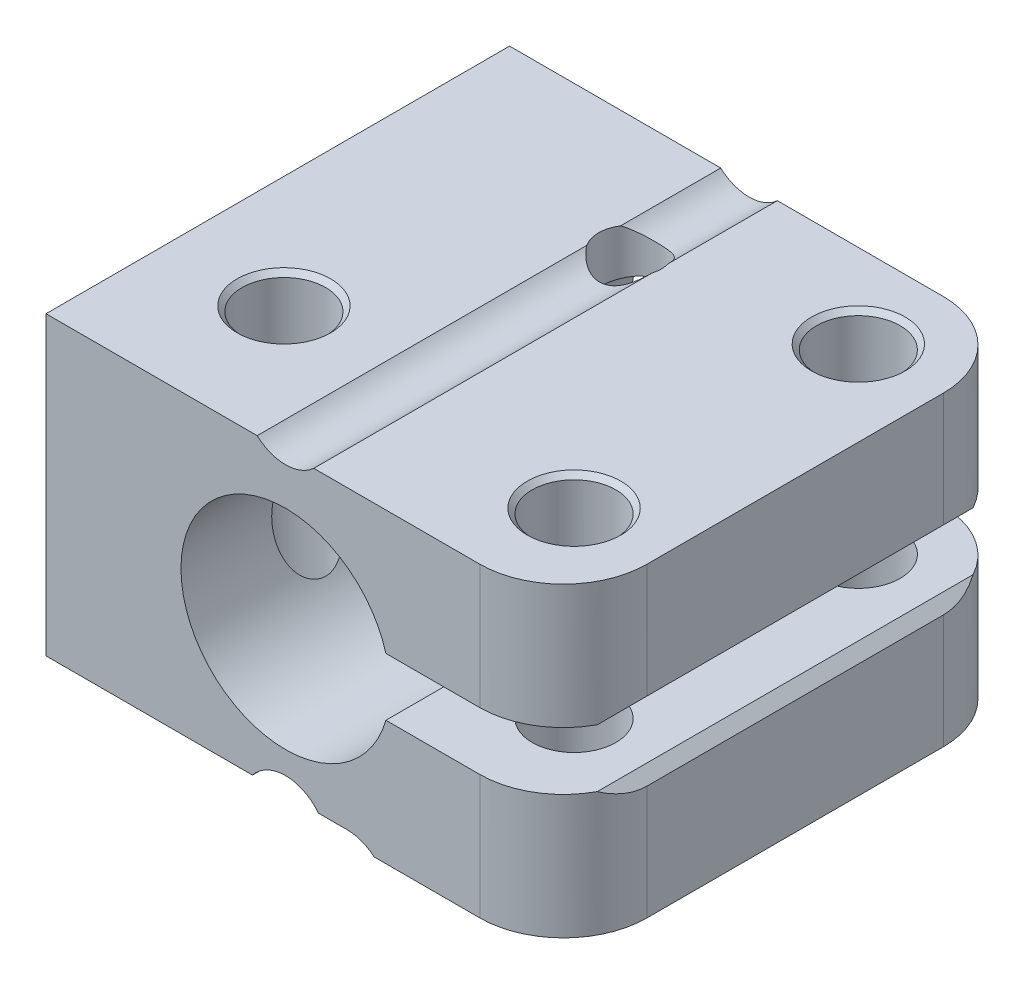
SolidWorks part; units mm, degrees
ref_plane "Front Plane" through (0, 0, 0) normal (0, 0, 1) x (1, 0, 0)
ref_plane "Top Plane" through (0, 0, 0) normal (0, 1, 0) x (1, 0, 0)
ref_plane "Right Plane" through (0, 0, 0) normal (1, 0, 0) x (0, 0, -1)
sketch "Sketch1" plane through (0, 0, 0) normal (0, 1, 0) x (1, 0, 0)
  line L1 (19.6469, -17.6022) -> (-19.6469, -17.6022)
  line L2 (19.6469, -17.6022) -> (19.6469, 17.6022)
  line L3 (19.6469, 17.6022) -> (-19.6469, 17.6022)
  line L4 (-19.6469, -17.6022) -> (-19.6469, 17.6022)
  line L5 (19.6469, -17.6022) -> (-19.6469, 17.6022) construction
  line L6 (19.6469, 17.6022) -> (-19.6469, -17.6022) construction
  point P0 (0, 0)
  dimension "D1" = 35.2044
  dimension "D2" = 39.2938
extrude "Boss-Extrude1" add sketch "Sketch1" along normal blind 23.2664
sketch "Sketch2" plane through (0, 0, -17.6022) normal (0, 0, -1) x (-1, 0, 0)
  line L0 (-19.6469, 11.6332) -> (19.6469, 11.6332) construction
  line L1 (-19.6469, 23.2664) -> (-19.6469, 0) construction
  line L2 (19.6469, 23.2664) -> (19.6469, 0) construction
  line L3 (-6.1669, 13.8303) -> (-19.6469, 13.8303)
  line L4 (-6.1669, 9.4361) -> (-19.6469, 9.4361)
  line L5 (-19.6469, 13.8303) -> (-19.6469, 9.4361)
  circle A0 centre (1.4605, 11.6332) radius 7.9375
  arc A1 (-6.1669, 13.8303) -> (-6.1669, 9.4361) centre (1.4605, 11.6332) ccw
  line M10 (-19.6469, 23.2664) -> (-19.6469, 0)
  dimension "D2" = 15.875
  dimension "D1" = 18.1864
  dimension "D3" = 2.1971
  dimension "D4" = 2.1971
extrude "Cut-Extrude1" cut sketch "Sketch2" against normal through all contours L0 L5 L4 A1 | L0 A0 L3 M10 | A0 L0 | L0 A1 A0
sketch "Sketch3" plane through (0, 0, -17.6022) normal (0, 0, -1) x (-1, 0, 0)
  circle A0 centre (1.4605, 11.6332) radius 8.4455
  arc A1 (-6.1669, 9.4361) -> (-6.1669, 13.8303) centre (1.4605, 11.6332) ccw construction
  point P2 (0, 0)
  dimension "D1" = 16.891
extrude "Cut-Extrude2" cut sketch "Sketch3" against normal blind 18.669
sketch "Sketch4" plane through (0, 0, 0) normal (0, -1, 0) x (1, 0, 0)
  line L0 (-1.6059, -17.6022) -> (-1.6059, 17.6022) construction
  line L1 (19.6469, -17.6022) -> (-19.6469, -17.6022) construction
  line L2 (-19.6469, 17.6022) -> (19.6469, 17.6022) construction
  line L3 (-9.906, -17.6022) -> (6.6942, -17.6022) construction
  circle A0 centre (13.1896, -11.2522) radius 3.175
  circle A1 centre (13.1896, 10.3378) radius 3.175
  circle A2 centre (-1.6059, -8.7122) radius 2.3813
  circle A3 centre (-11.1309, 8.0518) radius 3.175
  point P12 (-1.6059, -17.6022)
  dimension "D1" = 6.35
  dimension "D5" = 4.7625
  dimension "D7" = 6.35
  dimension "D2" = 6.35
  dimension "D3" = 21.59
  dimension "D4" = 14.7955
  dimension "D6" = 8.89
  dimension "D8" = 9.525
  dimension "D9" = 25.654
extrude "Cut-Extrude3" cut sketch "Sketch4" against normal through all
sketch "Sketch5" plane through (0, 0, -17.6022) normal (0, 0, -1) x (-1, 0, 0)
  line L0 (-19.6469, 23.2664) -> (19.6469, 23.2664) construction
  line L1 (-0.6889, 23.2664) -> (3.6099, 23.2664)
  arc A0 (-0.6889, 23.2664) -> (3.6099, 23.2664) centre (1.4605, 25.6032) ccw
  arc A1 (-6.6942, 9.4361) -> (-6.6942, 13.8303) centre (1.4605, 11.6332) ccw construction
  point P6 (1.4605, 11.6332)
  dimension "D1" = 3.175
  dimension "D2" = 13.97
extrude "Cut-Extrude4" cut sketch "Sketch5" against normal through all
sketch "Sketch7" plane through (0, 0, -17.6022) normal (0, 0, -1) x (-1, 0, 0)
  line L0 (19.6469, 0.762) -> (-3.2131, 0.762)
  line L1 (19.6469, 23.2664) -> (19.6469, 0) construction
  line L2 (-19.6469, 0) -> (19.6469, 0) construction
  line L3 (-5.2766, 0) -> (19.6469, 0)
  line L4 (19.6469, 0) -> (19.6469, 0.762)
  arc A0 (-6.6942, 9.4361) -> (-6.6942, 13.8303) centre (1.4605, 11.6332) ccw construction
  arc A1 (-3.2131, 0.762) -> (-5.2766, 0) centre (-3.2131, -2.413) ccw
  arc A2 (-1.0432, 0.762) -> (3.9642, 0.762) centre (1.4605, -1.1905) cw
  point P0 (1.4605, 11.6332)
  point P17 (0, 0)
  point P18 (3.9642, 0.762)
  line M13 (-19.6469, 0) -> (19.6469, 0)
  line M14 (19.6469, 0) -> (19.6469, 23.2664)
  dimension "D1" = 3.175
  dimension "D4" = 3.175
  dimension "D2" = 0.762
  dimension "D3" = 22.86
  dimension "D5" = 12.8237
extrude "Cut-Extrude5" cut sketch "Sketch7" against normal through all contours A2 L0 | L0 A1 M13 M14
fillet "Fillet1" radius 6.35 4 edges at (19.6469, 18.5483, 17.6022) (19.6469, 4.718, 17.6022) (19.6469, 4.718, -17.6022) (19.6469, 18.5483, -17.6022)
chamfer "Chamfer1" distance 0.508 angle 45 1 edges at (-9.906, 11.6332, -17.6022)
chamfer "Chamfer2" distance 0.381 angle 45 6 edges at (-11.1309, 23.2664, 4.8768) (13.1896, 23.2664, -14.4272) (13.1896, 23.2664, 7.1628) (-14.3059, 0.762, 8.0518) (13.1896, 0, 7.1628) (13.1896, 0, -14.4272)
sketch "Sketch8" plane through (0, 0, 0) normal (0, 0, 1) x (1, 0, 0)
  line L0 (18.8849, 13.8303) -> (19.6469, 14.5923)
  line L1 (13.2969, 13.8303) -> (19.6469, 13.8303) construction
  line L2 (19.6469, 23.2664) -> (19.6469, 13.8303) construction
  line L3 (19.6469, 14.5923) -> (19.6469, 13.8303)
  line L4 (19.6469, 13.8303) -> (18.8849, 13.8303)
  line L5 (18.8849, 9.4361) -> (19.6469, 8.6741)
  line L6 (19.6469, 9.4361) -> (13.2969, 9.4361) construction
  line L7 (19.6469, 9.4361) -> (19.6469, 0) construction
  line L8 (19.6469, 8.6741) -> (19.6469, 9.4361)
  line L9 (19.6469, 9.4361) -> (18.8849, 9.4361)
  dimension "D1" = 0.762
extrude "Cut-Extrude6" cut sketch "Sketch8" against normal through all and the other way through all
